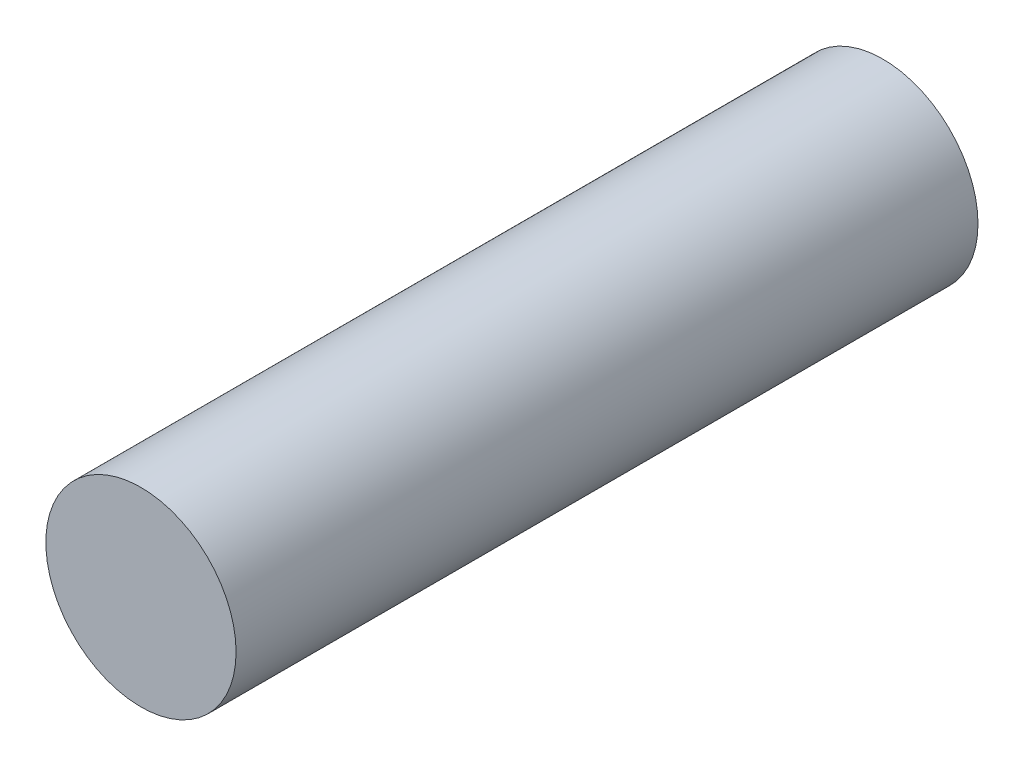
SolidWorks part; units mm, degrees
ref_plane "Front Plane" through (0, 0, 0) normal (0, 0, 1) x (1, 0, 0)
ref_plane "Top Plane" through (0, 0, 0) normal (0, 1, 0) x (1, 0, 0)
ref_plane "Right Plane" through (0, 0, 0) normal (1, 0, 0) x (0, 0, -1)
sketch "Sketch1" plane through (0, 0, 0) normal (0, 0, 1) x (1, 0, 0)
  circle A0 centre (0, 0) radius 2.5
  dimension "D1" = 5
extrude "Boss-Extrude1" add sketch "Sketch1" along normal blind 19.5
